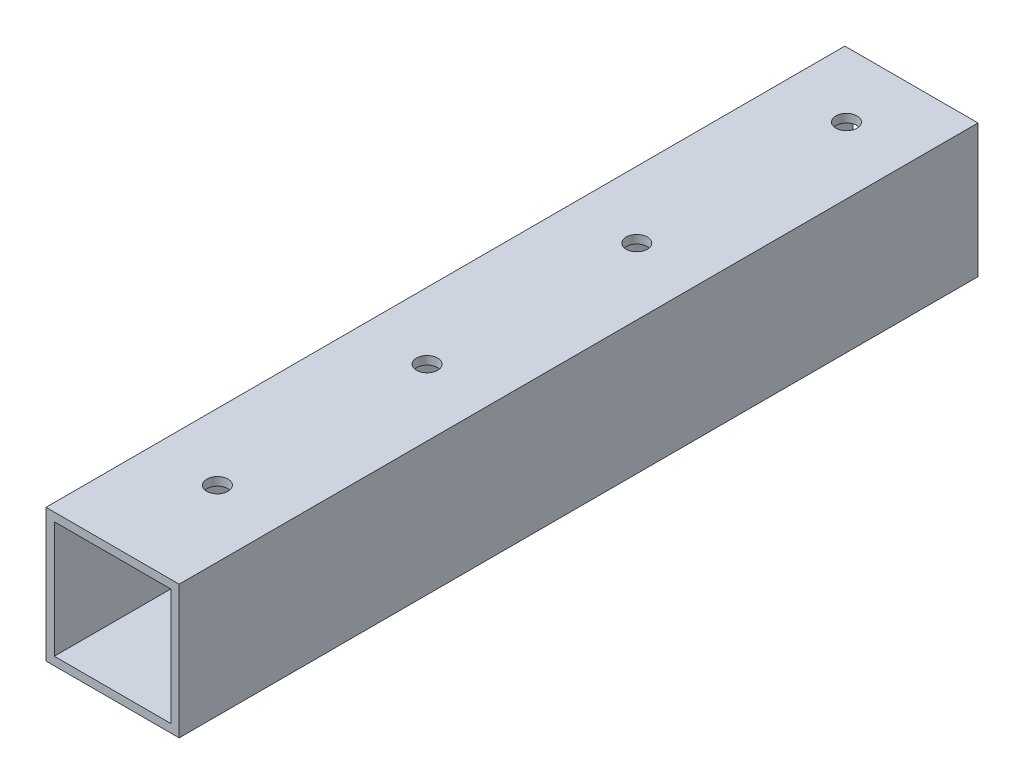
SolidWorks part; units mm, degrees
ref_plane "Front Plane" through (0, 0, 0) normal (0, 0, 1) x (1, 0, 0)
ref_plane "Top Plane" through (0, 0, 0) normal (0, 1, 0) x (1, 0, 0)
ref_plane "Right Plane" through (0, 0, 0) normal (1, 0, 0) x (0, 0, -1)
sketch "Sketch1" plane through (0, 0, 0) normal (0, 0, 1) x (1, 0, 0)
  line L1 (-25.4, 25.4) -> (25.4, 25.4)
  line L2 (-25.4, 25.4) -> (-25.4, -25.4)
  line L3 (-25.4, -25.4) -> (25.4, -25.4)
  line L4 (25.4, 25.4) -> (25.4, -25.4)
  line L5 (-25.4, 25.4) -> (25.4, -25.4) construction
  line L6 (-25.4, -25.4) -> (25.4, 25.4) construction
  line L7 (-22.225, 22.225) -> (22.225, 22.225)
  line L8 (-22.225, 22.225) -> (-22.225, -22.225)
  line L9 (-22.225, -22.225) -> (22.225, -22.225)
  line L10 (22.225, 22.225) -> (22.225, -22.225)
  line L11 (-22.225, 22.225) -> (22.225, -22.225) construction
  line L12 (-22.225, -22.225) -> (22.225, 22.225) construction
  point P0 (0, 0)
  point P6 (0, 0)
  dimension "D1" = 3.175
  dimension "D2" = 50.8
extrude "Boss-Extrude1" add sketch "Sketch1" against normal blind 304.8
sketch "Sketch2" plane through (0, 0, 0) normal (0, 1, 0) x (1, 0, 0)
  line L0 (0, 0) -> (0, 304.8) construction
  line L1 (25.4, 304.8) -> (-25.4, 304.8) construction
  circle A0 centre (0, 40) radius 4.05
  circle A1 centre (0, 120) radius 4.05
  circle A2 centre (0, 200) radius 4.05
  circle A3 centre (0, 280) radius 4.05
  dimension "D1" = 8.1
  dimension "D2" = 40
  dimension "D3" = 4
extrude "Cut-Extrude1" cut sketch "Sketch2" against normal blind 304.8 and the other way blind 304.8
